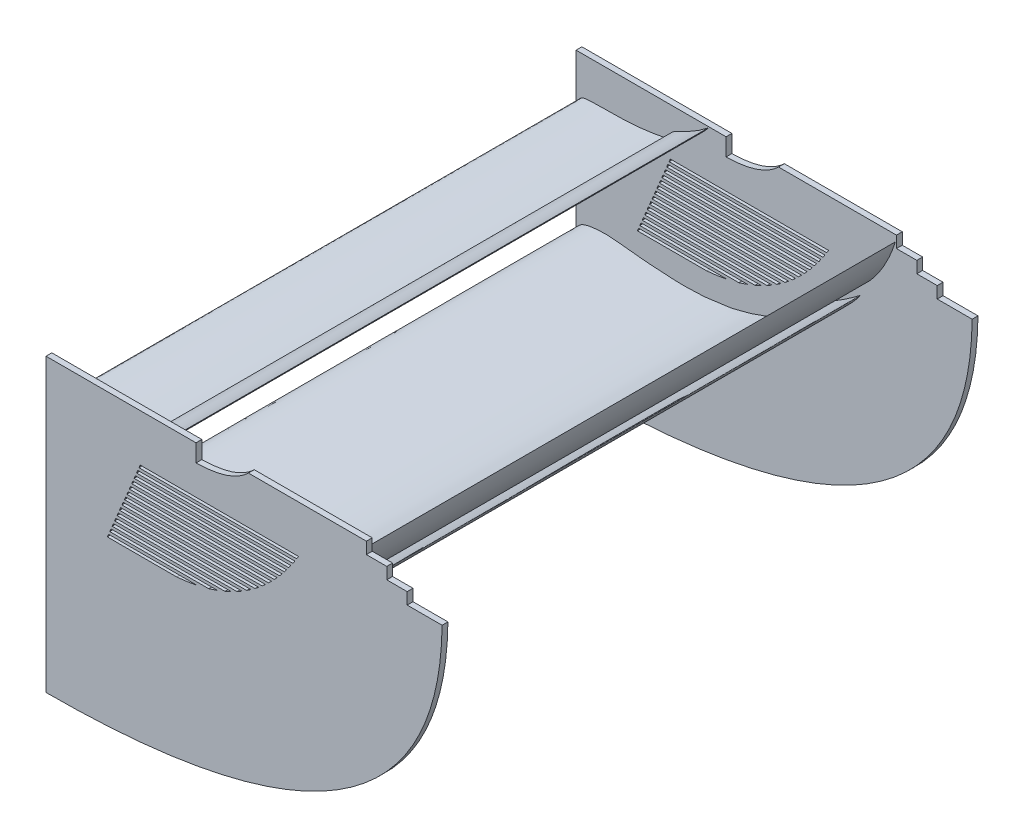
SolidWorks part; units mm, degrees
ref_plane "Front Plane" through (0, 0, 0) normal (0, 0, 1) x (1, 0, 0)
ref_plane "Top Plane" through (0, 0, 0) normal (0, 1, 0) x (1, 0, 0)
ref_plane "Right Plane" through (0, 0, 0) normal (1, 0, 0) x (0, 0, -1)
sketch "Sketch1" plane through (0, 0, 0) normal (0, 0, 1) x (1, 0, 0)
  line L0 (46.9575, 64.3181) -> (1074.8558, 208.7798) construction
sketch "Sketch2" plane through (0, 0, 0) normal (0, 0, 1) x (1, 0, 0)
  line L0 (0, 0) -> (400, 0) construction
  line L1 (0, 0) -> (399.6225, 66.8739) construction
  line L2 (0, 66.8739) -> (0, -66.8739) construction
  line L3 (10.0115, 66.8739) -> (10.0115, -116.1581) construction
  line L4 (20.0229, 66.8739) -> (20.0229, -116.1581) construction
  line L5 (30.0344, 66.8739) -> (30.0344, -116.1581) construction
  line L6 (40.0459, 66.8739) -> (40.0459, -116.1581) construction
  line L7 (50.0573, 66.8739) -> (50.0573, -116.1581) construction
  line L8 (60.0688, 66.8739) -> (60.0688, -116.1581) construction
  line L9 (70.0803, 66.8739) -> (70.0803, -116.1581) construction
  line L10 (80.0918, 66.8739) -> (80.0918, -116.1581) construction
  line L11 (90.1032, 66.8739) -> (90.1032, -116.1581) construction
  line L12 (100.1147, 66.8739) -> (100.1147, -116.1581) construction
  line L13 (110.1262, 66.8739) -> (110.1262, -116.1581) construction
  line L14 (120.1376, 66.8739) -> (120.1376, -116.1581) construction
  line L15 (130.1491, 66.8739) -> (130.1491, -116.1581) construction
  line L16 (140.1606, 66.8739) -> (140.1606, -116.1581) construction
  line L17 (150.172, 66.8739) -> (150.172, -116.1581) construction
  line L18 (160.1835, 66.8739) -> (160.1835, -116.1581) construction
  line L19 (170.195, 66.8739) -> (170.195, -116.1581) construction
  line L20 (180.2064, 66.8739) -> (180.2064, -116.1581) construction
  line L21 (190.2179, 66.8739) -> (190.2179, -116.1581) construction
  line L22 (200.2294, 66.8739) -> (200.2294, -116.1581) construction
  line L23 (210.2408, 66.8739) -> (210.2408, -116.1581) construction
  line L24 (220.2523, 66.8739) -> (220.2523, -116.1581) construction
  line L25 (230.2638, 66.8739) -> (230.2638, -116.1581) construction
  line L26 (240.2753, 66.8739) -> (240.2753, -116.1581) construction
  line L27 (250.2867, 66.8739) -> (250.2867, -116.1581) construction
  line L28 (260.2982, 66.8739) -> (260.2982, -116.1581) construction
  line L29 (270.3097, 66.8739) -> (270.3097, -116.1581) construction
  line L30 (280.3211, 66.8739) -> (280.3211, -116.1581) construction
  line L31 (290.3326, 66.8739) -> (290.3326, -116.1581) construction
  line L32 (300.3441, 66.8739) -> (300.3441, -116.1581) construction
  line L33 (310.3555, 66.8739) -> (310.3555, -116.1581) construction
  line L34 (320.367, 66.8739) -> (320.367, -116.1581) construction
  line L35 (330.3785, 66.8739) -> (330.3785, -116.1581) construction
  line L36 (340.3899, 66.8739) -> (340.3899, -116.1581) construction
  line L37 (350.4014, 66.8739) -> (350.4014, -116.1581) construction
  line L38 (360.4129, 66.8739) -> (360.4129, -116.1581) construction
  line L39 (370.4243, 66.8739) -> (370.4243, -116.1581) construction
  line L40 (380.4358, 66.8739) -> (380.4358, -116.1581) construction
  line L41 (390.4473, 66.8739) -> (390.4473, -116.1581) construction
  line L42 (400.4588, 66.8739) -> (400.4588, -116.1581) construction
  line L43 (836.1007, 66.8739) -> (-36.8556, 66.8739) construction
  line L44 (389.6225, 76.8739) -> (409.6225, 76.8739) construction
  line L45 (399.6225, 90.7703) -> (399.6225, 62.9774) construction
  line L46 (548.1427, 255.362) -> (478.7399, 156.2446) construction
  line L47 (488.7399, 146.2766) -> (482.6971, 142.1346) construction
  line L48 (389.6225, 76.8739) -> (488.7399, 146.2766) construction
  line L51 (488.7399, 194.8045) -> (488.7399, 123.7678) construction
  line L52 (478.7399, 201.6203) -> (478.7399, 116.9521) construction
  line L53 (478.7399, 156.2446) -> (614.5057, 156.2446) construction
  line L54 (389.6225, 83.3039) -> (389.6225, -27.4023) construction
  line L55 (478.7399, 146.2446) -> (614.5057, 146.2446) construction
  spline S0 degree 3 poles (8.4176, 12.2629) (-5.1, -0.6947) (8.0175, -15.4806) (19.5512, -21.724) (30.0167, -25.3022) (39.86, -28.8642) (50.0404, -30.6629) (60.0706, -32.2577) (70.0139, -34.2177) (80.101, -34.56) (90.0931, -35.3652) (100.112, -35.9529) (110.1282, -35.5072) (120.1532, -35.21) (130.1503, -34.2298) (140.19, -33.4102) (150.1782, -31.9134) (160.1704, -30.3713) (170.2408, -29.1636) (180.2083, -27.151) (190.2638, -25.3061) (200.2392, -22.8725) (210.2446, -20.4291) (220.2329, -17.8951) (230.3811, -15.7054) (240.3519, -12.3911) (253.5512, -7.3696) (266.9476, -2.8065) (280.4369, 1.6366) (290.3614, 5.8195) (300.4407, 10.0322) (310.3048, 14.8841) (323.8214, 20.8842) (337.3023, 27.2498) (350.2747, 34.8502) (364.0374, 41.2007) (378.0734, 50.4319) (389.2687, 56.9917) (404.9331, 70.6704) (388.8931, 60.8973) (380.9617, 56.8333) (370.3166, 52.1732) (360.4136, 47.7491) (350.4697, 43.0754) (340.4967, 38.8332) (330.4052, 35.261) (320.3498, 31.8494) (310.3583, 28.3259) (300.4869, 24.6622) (290.3218, 22.3006) (280.2904, 19.7619) (270.4267, 16.765) (260.336, 15.0613) (250.2769, 13.9588) (240.2662, 12.5783) (230.2787, 11.0679) (220.2867, 9.6964) (210.2433, 9.2404) (200.2287, 9.0345) (190.217, 8.2792) (180.2125, 9.1624) (170.1842, 8.7285) (160.1865, 9.5822) (150.1678, 9.9892) (140.1635, 10.7007) (130.146, 11.2145) (120.1214, 11.8409) (110.1328, 12.9697) (100.1148, 13.8501) (90.0938, 14.7159) (80.0796, 15.8427) (56.9177, 18.8475) (32.3828, 18.9634) (8.4176, 12.2629) (-5.1, -0.6947) (8.0175, -15.4806) knots -0.089629 -0.030705 -0.018228 0 0.022024 0.035622 0.048197 0.060585 0.072602 0.084545 0.096479 0.108284 0.12009 0.131879 0.143661 0.155449 0.167269 0.1791 0.190991 0.202897 0.214788 0.226766 0.238768 0.250864 0.262992 0.27512 0.287235 0.299601 0.31215 0.337082 0.349542 0.362249 0.375072 0.388091 0.40103 0.427261 0.440709 0.453892 0.481344 0.495528 0.510184 0.522428 0.535733 0.548643 0.561554 0.574511 0.587287 0.599816 0.612271 0.624763 0.637218 0.649381 0.661544 0.67375 0.685718 0.697586 0.709472 0.721375 0.733243 0.74504 0.756824 0.768611 0.780398 0.792175 0.803972 0.815766 0.827567 0.839363 0.851169 0.863006 0.874833 0.88666 0.89851 0.910371 0.969295 0.981772 1 1.022024 1.035622 1.048197 only from (0, 0) to (0, 0)
  spline S1 degree 3 poles (488.4807, 145.9571) (488.8121, 146.3498) (488.4243, 146.015) (488.0622, 145.7851) (487.2625, 145.1263) (486.2197, 144.3713) (484.8735, 143.3367) (483.2507, 142.1161) (481.3449, 140.7026) (479.1839, 139.1083) (476.7613, 137.3643) (474.1237, 135.4494) (471.2368, 133.4393) (468.1657, 131.2913) (464.8962, 129.0676) (461.4575, 126.7695) (457.874, 124.4106) (454.1513, 122.027) (450.3296, 119.6083) (446.4184, 117.1921) (442.4423, 114.7926) (438.4319, 112.4153) (434.4211, 110.0589) (430.4193, 107.7484) (426.4691, 105.4752) (422.5724, 103.27) (418.7829, 101.1054) (415.1038, 99.0189) (411.5811, 96.98) (408.2231, 95.0247) (405.0701, 93.1172) (402.1178, 91.3128) (399.4157, 89.5543) (396.9653, 87.8935) (394.7924, 86.3186) (392.9158, 84.83) (391.3498, 83.4309) (390.0835, 82.1509) (389.1526, 80.9646) (388.5665, 79.872) (388.3105, 78.8689) (388.4525, 77.9475) (389.0134, 77.2045) (389.9156, 76.685) (391.1282, 76.3842) (392.6501, 76.2546) (394.4851, 76.3138) (396.6232, 76.5794) (399.0459, 77.0357) (401.7358, 77.7205) (404.6757, 78.5968) (407.8392, 79.7049) (411.2008, 81.0269) (414.7209, 82.591) (418.3956, 84.3418) (422.1799, 86.3091) (426.0457, 88.48) (429.9704, 90.8288) (433.915, 93.3645) (437.8712, 96.0402) (441.7934, 98.8661) (445.6685, 101.7972) (449.4657, 104.8272) (453.1679, 107.924) (456.7615, 111.054) (460.2029, 114.2195) (463.5191, 117.343) (466.6501, 120.455) (469.6136, 123.4898) (472.3702, 126.4509) (474.954, 129.2656) (477.2978, 131.9605) (479.4562, 134.4635) (481.3811, 136.7846) (483.0779, 138.8974) (484.5577, 140.7696) (485.8099, 142.3825) (486.8479, 143.7389) (487.6258, 144.7686) (488.2511, 145.5957) (488.4807, 145.9571) (488.8121, 146.3498) (488.4243, 146.015) knots -0.00692 -0.003098 -0.00077 0 0.000781 0.003074 0.006931 0.012248 0.01903 0.027226 0.036785 0.04761 0.059602 0.072764 0.086897 0.102004 0.117939 0.134556 0.151858 0.169651 0.187838 0.206374 0.225065 0.243814 0.262569 0.281137 0.299514 0.317506 0.335105 0.352118 0.368488 0.384167 0.398955 0.412906 0.425872 0.437811 0.448585 0.458213 0.466669 0.473884 0.479894 0.484779 0.488743 0.492167 0.495628 0.499576 0.504487 0.510576 0.517943 0.526574 0.536524 0.54764 0.560015 0.573491 0.588031 0.603544 0.619912 0.637089 0.654944 0.673346 0.692212 0.711461 0.73091 0.750475 0.770022 0.789461 0.808651 0.827458 0.84582 0.863559 0.880666 0.896945 0.912322 0.926718 0.939993 0.952161 0.96306 0.972662 0.980906 0.987733 0.99308 0.996902 0.99923 1 1.000781 1.003074 1.006931 only from (488.7399, 146.2766) to (488.7399, 146.2766)
  spline S2 degree 3 poles (548.0012, 254.9703) (548.1874, 255.456) (547.9279, 255.0069) (547.6584, 254.6667) (547.113, 253.7707) (546.3674, 252.702) (545.4246, 251.265) (544.2794, 249.5582) (542.9279, 247.5728) (541.3924, 245.3297) (539.6567, 242.8564) (537.7725, 240.1482) (535.6814, 237.266) (533.4602, 234.1907) (531.0746, 230.977) (528.5519, 227.6359) (525.9111, 224.1885) (523.1453, 220.6711) (520.2967, 217.0873) (517.3615, 213.4761) (514.3589, 209.8593) (511.316, 206.2523) (508.2658, 202.665) (505.209, 199.1247) (502.189, 195.6372) (499.1976, 192.2326) (496.2952, 188.9024) (493.4722, 185.6835) (490.783, 182.5623) (488.2235, 179.5757) (485.844, 176.7031) (483.6219, 173.9957) (481.6239, 171.4156) (479.834, 169.0126) (478.2807, 166.784) (476.9821, 164.7365) (475.9505, 162.878) (475.1658, 161.233) (474.6707, 159.7892) (474.4739, 158.5497) (474.5629, 157.5056) (475.0053, 156.672) (475.7887, 156.1483) (476.824, 155.9518) (478.0833, 156.0678) (479.5813, 156.4503) (481.3159, 157.1174) (483.2715, 158.0828) (485.4358, 159.3251) (487.7794, 160.8747) (490.2983, 162.6906) (492.9538, 164.8026) (495.7276, 167.1848) (498.5723, 169.8513) (501.5026, 172.7478) (504.4658, 175.8877) (507.4391, 179.2493) (510.4095, 182.8005) (513.3367, 186.5371) (516.2285, 190.4114) (519.0377, 194.4179) (521.767, 198.5093) (524.3889, 202.6695) (526.8977, 206.8618) (529.2916, 211.0497) (531.5283, 215.2209) (533.6592, 219.3103) (535.617, 223.3271) (537.4402, 227.2144) (539.0902, 230.9623) (540.6237, 234.5128) (541.9677, 237.8689) (543.1982, 240.9799) (544.2661, 243.8393) (545.1852, 246.4237) (545.977, 248.7058) (546.6373, 250.6644) (547.1783, 252.3065) (547.5794, 253.5497) (547.9019, 254.5484) (548.0012, 254.9703) (548.1874, 255.456) (547.9279, 255.0069) knots -0.00692 -0.003098 -0.00077 0 0.000781 0.003074 0.006931 0.012248 0.01903 0.027226 0.036785 0.04761 0.059602 0.072764 0.086897 0.102004 0.117939 0.134556 0.151858 0.169651 0.187838 0.206374 0.225065 0.243814 0.262569 0.281137 0.299514 0.317506 0.335105 0.352118 0.368488 0.384167 0.398955 0.412906 0.425872 0.437811 0.448585 0.458213 0.466669 0.473884 0.479894 0.484779 0.488743 0.492167 0.495628 0.499576 0.504487 0.510576 0.517943 0.526574 0.536524 0.54764 0.560015 0.573491 0.588031 0.603544 0.619912 0.637089 0.654944 0.673346 0.692212 0.711461 0.73091 0.750475 0.770022 0.789461 0.808651 0.827458 0.84582 0.863559 0.880666 0.896945 0.912322 0.926718 0.939993 0.952161 0.96306 0.972662 0.980906 0.987733 0.99308 0.996902 0.99923 1 1.000781 1.003074 1.006931 only from (548.1427, 255.362) to (548.1427, 255.362)
  point P7 (0, 0)
  point P94 (399.6225, 76.8739)
  point P100 (399.6225, 76.8739)
  point P108 (399.6225, 66.8739)
  point P112 (389.6225, 76.8739)
  point P126 (488.7399, 146.2766)
  point P130 (488.7399, 156.2766)
  point P136 (488.7399, 159.2862)
  point P142 (478.7399, 159.2862)
  dimension "D1" = 9.5
  dimension "D3" = 405.1793
  dimension "D4" = 400
  dimension "D5" = 121
  dimension "D6" = 10
  dimension "D7" = 35
  dimension "D8" = 10
  dimension "D9" = 55
  dimension "D10" = 10
  dimension "D11" = 121
  dimension "D12" = 10
  dimension "D13" = 79.3707
  dimension "D2" = 41
extrude "Boss-Extrude1" add sketch "Sketch2" along normal blind 900
ref_plane "Plane1" through (0, 0, 900) normal (0, 0, 1) x (1, 0, 0)
sketch "Sketch5" plane through (0, 0, 0) normal (0, 0, 1) x (1, 0, 0)
  line L0 (550, 266.2835) -> (550, -233.7165) construction
  line L1 (0, 266.2835) -> (550, 266.2835)
  line L2 (0, 266.2835) -> (0, 0)
  line L5 (550, 266.2835) -> (550, 246.2835)
  line L6 (550, 246.2835) -> (585, 246.2835)
  line L7 (585, 246.2835) -> (585, 226.2835)
  line L8 (585, 226.2835) -> (620, 226.2835)
  line L9 (620, 226.2835) -> (620, 206.2835)
  line L10 (620, 206.2835) -> (680, 206.2835)
  line L11 (675, -233.7165) -> (425, -233.7165) construction
  line L12 (680, 206.2835) -> (675, -233.7165) construction
  line L13 (675, -233.7165) -> (0, -233.7165) construction
  line L14 (0, 0) -> (0, -233.7165)
  spline S0 degree 2 poles (680, 206.2835) (675, -233.7165) (0, -233.7165) knots 0 0 0 1 1 1
  point P6 (550, -233.7165)
  dimension "D1" = 500
  dimension "D2" = 125
  dimension "D3" = 35
  dimension "D4" = 20
  dimension "D5" = 20
  dimension "D6" = 35
  dimension "D7" = 20
  dimension "D8" = 60
  dimension "D9" = 675
  dimension "D10" = 440
ref_plane "Plane2" through (0, 0, 450) normal (0, 0, 1) x (1, 0, 0)
extrude "Boss-Extrude2" add sketch "Sketch5" against normal blind 10 contours L1 L5 L6 L7 L8 L9 L10 S0 L14 L2
sketch "Sketch6" plane through (0, 0, 0) normal (0, 0, 1) x (1, 0, 0)
  line L0 (0, 197.4544) -> (160, 197.4544) construction
  line L1 (0, 266.2835) -> (0, 0) construction
  line L2 (160, 197.4544) -> (258.2982, 266.2835) construction
  line L3 (0, 266.2835) -> (550, 266.2835) construction
  line L4 (164.6138, 214.9761) -> (164.7238, 214.6645)
  line L5 (164.6138, 214.9761) -> (8.3018, 197.4544) construction
  line L6 (8.3018, 197.4544) -> (160, 197.4544) construction
  line L7 (164.7238, 214.6645) -> (215.8682, 214.6645) construction
  line L8 (164.6138, 224.6645) -> (215.8682, 224.6645) construction
  line L9 (227.0142, 264.2269) -> (227.1245, 264.1177)
  line L10 (227.0142, 264.2269) -> (164.4495, 224.8752) construction
  spline S0 degree 3 poles (164.7238, 214.6645) (164.6485, 214.6279) (164.3478, 214.4816) (163.6724, 214.1552) (162.55, 213.6175) (160.9852, 212.8783) (158.985, 211.9502) (156.5581, 210.8501) (153.7156, 209.5966) (150.4706, 208.2115) (146.8388, 206.7177) (142.8379, 205.1402) (138.4882, 203.505) (133.8122, 201.8376) (128.8347, 200.165) (123.5829, 198.5127) (118.0862, 196.9059) (112.3762, 195.3683) (106.4862, 193.9228) (100.4517, 192.5894) (94.3097, 191.3873) (88.0988, 190.332) (81.8589, 189.4374) (75.6309, 188.7132) (69.4566, 188.1671) (63.3778, 187.8027) (57.4367, 187.6199) (51.6745, 187.6158) (46.1317, 187.7835) (40.8475, 188.1122) (35.859, 188.5889) (31.201, 189.198) (26.9054, 189.9203) (23.0013, 190.7368) (19.5141, 191.6263) (16.4656, 192.568) (13.8731, 193.5412) (11.7498, 194.5273) (10.1003, 195.5106) (8.9257, 196.4838) (8.2062, 197.4661) (8.027, 198.5089) (8.4702, 199.4674) (9.4095, 200.2316) (10.7736, 200.88) (12.5817, 201.4358) (14.8279, 201.9066) (17.5019, 202.295) (20.5864, 202.6069) (24.0614, 202.8473) (27.9044, 203.0253) (32.0912, 203.1493) (36.5959, 203.231) (41.3918, 203.282) (46.4505, 203.3154) (51.7431, 203.3445) (57.2393, 203.3835) (62.9083, 203.4456) (68.7179, 203.5435) (74.6355, 203.6891) (80.6273, 203.8921) (86.6588, 204.1602) (92.6952, 204.4989) (98.701, 204.9104) (104.6405, 205.3951) (110.4779, 205.9495) (116.1778, 206.5676) (121.7051, 207.2412) (127.0255, 207.9592) (132.1056, 208.7094) (136.9131, 209.4769) (141.4173, 210.2472) (145.589, 211.0042) (149.4009, 211.7324) (152.8279, 212.4165) (155.8468, 213.0419) (158.4374, 213.5952) (160.5819, 214.065) (162.2656, 214.441) (163.4767, 214.7155) (164.2068, 214.8826) (164.5322, 214.9574) (164.6138, 214.9761) knots 0 0 0 0 0.00078 0.003113 0.006984 0.012366 0.019224 0.027511 0.037173 0.048145 0.060358 0.073731 0.088182 0.103618 0.119946 0.137065 0.15487 0.173257 0.192113 0.211327 0.230786 0.250373 0.269972 0.289465 0.308737 0.32767 0.346151 0.364066 0.381307 0.397768 0.413347 0.427952 0.441493 0.45389 0.465074 0.474985 0.48358 0.490835 0.496756 0.501407 0.504969 0.507873 0.510777 0.514327 0.518939 0.524778 0.531895 0.540287 0.549922 0.560751 0.572712 0.585736 0.599745 0.614657 0.630386 0.646842 0.66393 0.681556 0.699621 0.718024 0.736663 0.755434 0.774231 0.792948 0.811476 0.829709 0.847536 0.864851 0.881546 0.897515 0.912656 0.926869 0.940056 0.952128 0.962998 0.972589 0.98083 0.98766 0.993027 0.996891 0.999221 1 1 1 1
  spline S1 degree 3 poles (227.1245, 264.1177) (227.1002, 264.0868) (227.003, 263.9634) (226.7842, 263.6871) (226.4198, 263.23) (225.9096, 262.5971) (225.2539, 261.7952) (224.4531, 260.8332) (223.508, 259.7213) (222.4196, 258.4713) (221.1899, 257.0962) (219.8214, 255.6101) (218.3172, 254.0282) (216.6816, 252.3659) (214.9197, 250.6397) (213.0376, 248.8659) (211.0426, 247.0612) (208.9433, 245.2421) (206.749, 243.4251) (204.4708, 241.6258) (202.1201, 239.8601) (199.7103, 238.1424) (197.2553, 236.4866) (194.7705, 234.9053) (192.2719, 233.4103) (189.7765, 232.0117) (187.302, 230.7181) (184.8667, 229.5366) (182.489, 228.4727) (180.1876, 227.5298) (177.9809, 226.71) (175.8869, 226.0139) (173.9229, 225.4398) (172.1051, 224.9857) (170.4487, 224.6478) (168.967, 224.4218) (167.6717, 224.3024) (166.5721, 224.2846) (165.6734, 224.3626) (164.9776, 224.5336) (164.4722, 224.8016) (164.183, 225.2058) (164.1741, 225.7018) (164.4148, 226.2172) (164.8587, 226.7706) (165.5094, 227.3758) (166.3627, 228.0347) (167.4137, 228.7464) (168.6539, 229.5097) (170.0739, 230.3229) (171.6622, 231.1849) (173.4069, 232.0945) (175.2947, 233.0513) (177.3119, 234.0548) (179.4438, 235.1046) (181.6755, 236.2005) (183.9912, 237.3423) (186.3753, 238.5292) (188.8115, 239.76) (191.2835, 241.0331) (193.7752, 242.3457) (196.2704, 243.6939) (198.7531, 245.073) (201.208, 246.4765) (203.6199, 247.8975) (205.9744, 249.327) (208.2576, 250.7553) (210.4566, 252.1717) (212.559, 253.5646) (214.5532, 254.9218) (216.4286, 256.2306) (218.1752, 257.4784) (219.784, 258.6526) (221.2465, 259.7409) (222.5553, 260.7317) (223.7036, 261.6142) (224.6856, 262.3786) (225.4961, 263.0162) (226.131, 263.5199) (226.5868, 263.8839) (226.8612, 264.104) (226.9835, 264.2023) (227.0142, 264.2269) knots 0 0 0 0 0.00078 0.003113 0.006984 0.012366 0.019224 0.027511 0.037173 0.048145 0.060358 0.073731 0.088182 0.103618 0.119946 0.137065 0.15487 0.173257 0.192113 0.211327 0.230786 0.250373 0.269972 0.289465 0.308737 0.32767 0.346151 0.364066 0.381307 0.397768 0.413347 0.427952 0.441493 0.45389 0.465074 0.474985 0.48358 0.490835 0.496756 0.501407 0.504969 0.507873 0.510777 0.514327 0.518939 0.524778 0.531895 0.540287 0.549922 0.560751 0.572712 0.585736 0.599745 0.614657 0.630386 0.646842 0.66393 0.681556 0.699621 0.718024 0.736663 0.755434 0.774231 0.792948 0.811476 0.829709 0.847536 0.864851 0.881546 0.897515 0.912656 0.926869 0.940056 0.952128 0.962998 0.972589 0.98083 0.98766 0.993027 0.996891 0.999221 1 1 1 1
  dimension "D1" = 145
  dimension "D2" = 160
  dimension "D3" = 120
  dimension "D4" = 10
extrude "Boss-Extrude3" add sketch "Sketch6" along normal blind 900
sketch "Sketch7" plane through (0, 0, 0) normal (0, 0, 1) x (1, 0, 0)
  line L0 (257.5301, 266.2835) -> (257.5301, 236.2835)
  line L1 (0, 266.2835) -> (550, 266.2835) construction
  line L2 (257.5301, 266.2835) -> (347.5301, 266.2835)
  line L3 (347.5301, 266.2835) -> (317.5714, 237.211) construction
  line L4 (317.5714, 237.211) -> (257.5301, 236.2835) construction
  spline S1 degree 2 poles (347.5301, 266.2835) (317.5714, 237.211) (257.5301, 236.2835) knots 0 0 0 1 1 1
  dimension "D1" = 30
  dimension "D2" = 90
extrude "Cut-Extrude1" cut sketch "Sketch7" against normal blind 900
sketch "Sketch8" plane through (0, 0, 0) normal (0, 0, 1) x (1, 0, 0)
  line L4 (161.8037, 185.2784) -> (433.5275, 185.2784)
  line L5 (159.7086, 180.2784) -> (430.4208, 180.2784)
  line L16 (164.9224, 130.2784) -> (452.6678, 130.2784) [skipped]
  line L26 (67.2058, 135.2784) -> (220.4617, 135.2784) [skipped]
  line L27 (76.1878, 140.2784) -> (244.1181, 140.2784) [skipped]
  line L28 (85.1699, 145.2784) -> (267.7746, 145.2784) [skipped]
  line L29 (94.1519, 150.2784) -> (291.431, 150.2784) [skipped]
  line L30 (103.1339, 155.2784) -> (315.0875, 155.2784) [skipped]
  line L31 (112.116, 160.2784) -> (338.7439, 160.2784) [skipped]
  line L32 (121.098, 165.2784) -> (362.4003, 165.2784) [skipped]
  line L33 (139.0621, 175.2784) -> (409.7132, 175.2784) [skipped]
  line L34 (130.08, 170.2784) -> (386.0568, 170.2784) [skipped]
  line L36 (155.5185, 170.2784) -> (423.8746, 170.2784)
  line L37 (157.6135, 175.2784) -> (427.2053, 175.2784)
  line L40 (151.3284, 160.2784) -> (416.8376, 160.2784)
  line L41 (153.4234, 165.2784) -> (420.4214, 165.2784)
  line L44 (147.1382, 150.2784) -> (409.2419, 150.2784)
  line L45 (149.2333, 155.2784) -> (413.1145, 155.2784)
  line L48 (142.9481, 140.2784) -> (401.0022, 140.2784)
  line L49 (145.0432, 145.2784) -> (405.2087, 145.2784)
  line L52 (138.758, 130.2784) -> (392.0089, 130.2784)
  line L53 (140.853, 135.2784) -> (396.6078, 135.2784)
  line L56 (134.5679, 120.2784) -> (382.1176, 120.2784)
  line L57 (136.6629, 125.2784) -> (387.1863, 125.2784)
  line L60 (130.3777, 110.2784) -> (371.1304, 110.2784)
  line L61 (132.4728, 115.2784) -> (376.7761, 115.2784)
  line L64 (126.1876, 100.2784) -> (358.7645, 100.2784)
  line L65 (128.2827, 105.2784) -> (365.1422, 105.2784)
  line L68 (121.9975, 90.2784) -> (344.5889, 90.2784)
  line L69 (124.0926, 95.2784) -> (351.9385, 95.2784)
  line L72 (117.8074, 80.2784) -> (327.8864, 80.2784)
  line L73 (119.9024, 85.2784) -> (336.6165, 85.2784)
  line L76 (113.6173, 70.2784) -> (307.2861, 70.2784)
  line L77 (115.7123, 75.2784) -> (318.2064, 75.2784)
  line L80 (109.4271, 60.2784) -> (279.3938, 60.2784)
  line L81 (111.5222, 65.2784) -> (294.6475, 65.2784)
  line L84 (105.237, 50.2784) -> (224.5387, 50.2784)
  line L85 (107.3321, 55.2784) -> (259.3865, 55.2784)
  line L88 (161.8037, 185.2784) -> (159.7086, 180.2784)
  line L89 (119.9024, 85.2784) -> (117.8074, 80.2784)
  line L114 (107.3321, 55.2784) -> (105.237, 50.2784)
  line L115 (111.5222, 65.2784) -> (109.4271, 60.2784)
  line L116 (115.7123, 75.2784) -> (113.6173, 70.2784)
  line L117 (124.0926, 95.2784) -> (121.9975, 90.2784)
  line L118 (128.2827, 105.2784) -> (126.1876, 100.2784)
  line L119 (132.4728, 115.2784) -> (130.3777, 110.2784)
  line L120 (157.6135, 175.2784) -> (155.5185, 170.2784)
  line L121 (153.4234, 165.2784) -> (151.3284, 160.2784)
  line L122 (149.2333, 155.2784) -> (147.1382, 150.2784)
  line L123 (145.0432, 145.2784) -> (142.9481, 140.2784)
  line L124 (140.853, 135.2784) -> (138.758, 130.2784)
  line L125 (136.6629, 125.2784) -> (134.5679, 120.2784)
  spline S0 degree 2 poles (433.5275, 185.2784) (431.986, 182.755) (430.4208, 180.2784) knots 0 0 0 0.017044 0.017044 0.017044
  spline S1 degree 3 poles (420.4214, 165.2784) (419.2361, 163.5933) (418.0415, 161.9267) (416.8376, 160.2784) knots 0.070227 0.070227 0.070227 0.070227 0.088712 0.088712 0.088712 0.088712
  spline S2 degree 3 poles (427.2053, 175.2784) (426.1036, 173.5948) (424.9934, 171.9282) (423.8746, 170.2784) knots 0.034417 0.034417 0.034417 0.034417 0.052137 0.052137 0.052137 0.052137
  spline S3 degree 3 poles (413.1145, 155.2784) (411.8338, 153.5916) (410.543, 151.9249) (409.2419, 150.2784) knots 0.107617 0.107617 0.107617 0.107617 0.126974 0.126974 0.126974 0.126974
  spline S4 degree 3 poles (405.2087, 145.2784) (403.8178, 143.5894) (402.4157, 141.9228) (401.0022, 140.2784) knots 0.146816 0.146816 0.146816 0.146816 0.167181 0.167181 0.167181 0.167181
  spline S5 degree 3 poles (396.6078, 135.2784) (395.0875, 133.5868) (393.5545, 131.9201) (392.0089, 130.2784) knots 0.188113 0.188113 0.188113 0.188113 0.209663 0.209663 0.209663 0.209663
  spline S6 degree 3 poles (387.1863, 125.2784) (385.5111, 123.5834) (383.8215, 121.9167) (382.1176, 120.2784) knots 0.231889 0.231889 0.231889 0.231889 0.254857 0.254857 0.254857 0.254857
  spline S7 degree 3 poles (376.7761, 115.2784) (374.9109, 113.5789) (373.029, 111.9122) (371.1304, 110.2784) knots 0.27865 0.27865 0.27865 0.27865 0.303361 0.303361 0.303361 0.303361
  spline S8 degree 3 poles (365.1422, 105.2784) (363.0361, 103.5728) (360.9102, 101.9061) (358.7645, 100.2784) knots 0.329106 0.329106 0.329106 0.329106 0.356027 0.356027 0.356027 0.356027
  spline S9 degree 3 poles (351.9385, 95.2784) (349.5129, 93.5638) (347.0631, 91.8972) (344.5889, 90.2784) knots 0.384302 0.384302 0.384302 0.384302 0.414159 0.414159 0.414159 0.414159
  spline S10 degree 3 poles (336.6165, 85.2784) (333.738, 83.5495) (330.828, 81.8829) (327.8864, 80.2784) knots 0.445896 0.445896 0.445896 0.445896 0.47992 0.47992 0.47992 0.47992
  spline S11 degree 3 poles (318.2064, 75.2784) (314.6113, 73.523) (310.9712, 71.8563) (307.2861, 70.2784) knots 0.516814 0.516814 0.516814 0.516814 0.557452 0.557452 0.557452 0.557452
  spline S12 degree 3 poles (294.6475, 65.2784) (289.6416, 63.4567) (284.557, 61.79) (279.3938, 60.2784) knots 0.60328 0.60328 0.60328 0.60328 0.657004 0.657004 0.657004 0.657004
  spline S13 degree 3 poles (259.3865, 55.2784) (248.1179, 52.9273) (236.502, 51.2606) (224.5387, 50.2784) knots 0.725082 0.725082 0.725082 0.725082 0.837974 0.837974 0.837974 0.837974
  dimension "D1" = 14
  dimension "D6" = 12
extrude "Cut-Extrude2" cut sketch "Sketch8" against normal blind 900
mirror "Mirror1" about plane through (0, 0, 450) normal (0, 0, 1) of "Cut-Extrude2", "Cut-Extrude1", "Boss-Extrude2"
